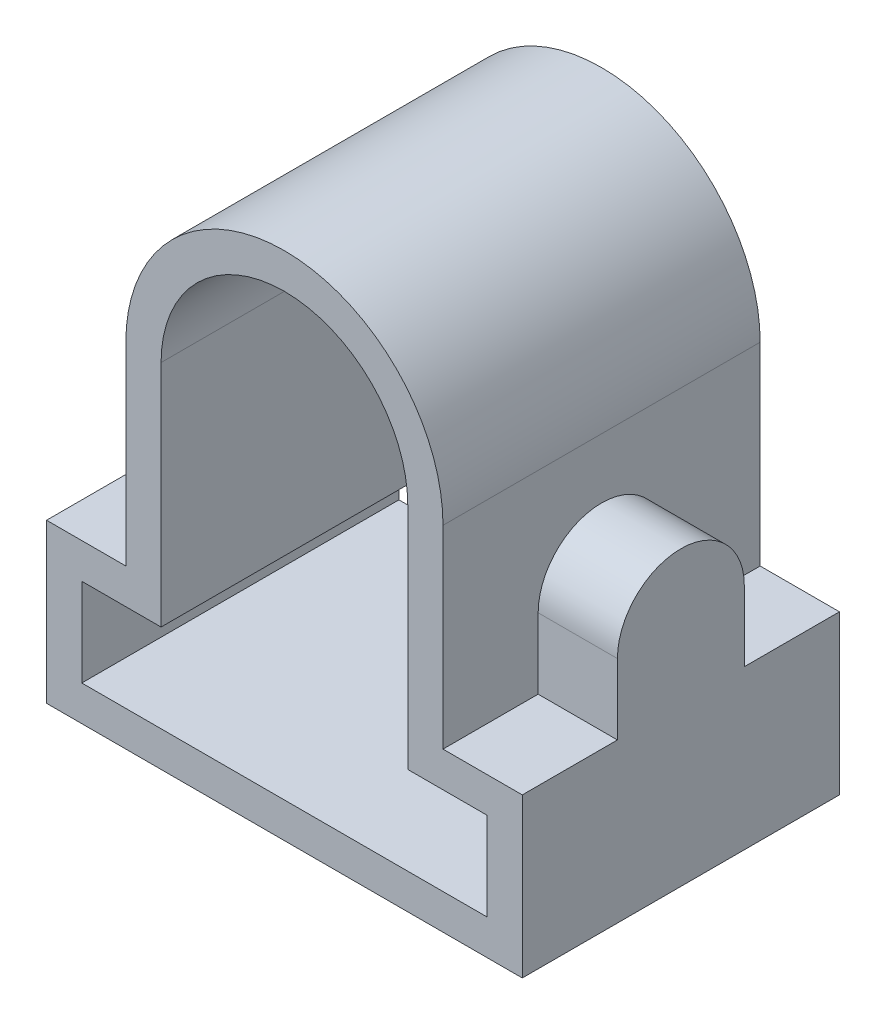
SolidWorks part; units mm, degrees
ref_plane "Płaszczyzna przednia" through (0, 0, 0) normal (0, 0, 1) x (1, 0, 0)
ref_plane "Płaszczyzna górna" through (0, 0, 0) normal (0, 1, 0) x (1, 0, 0)
ref_plane "Płaszczyzna prawa" through (0, 0, 0) normal (1, 0, 0) x (0, 0, -1)
sketch "Szkic1" plane through (0, 0, 0) normal (0, 0, 1) x (1, 0, 0)
  line L0 (0, 0) -> (0, 100) construction
  line L1 (67.5, 0) -> (-67.5, 0)
  line L2 (-67.5, 0) -> (-67.5, 45)
  line L3 (-67.5, 45) -> (-45, 45)
  line L4 (-45, 45) -> (-45, 100)
  line L5 (67.5, 0) -> (67.5, 45)
  line L6 (67.5, 45) -> (45, 45)
  line L7 (45, 45) -> (45, 100)
  line L8 (35, 35) -> (35, 100)
  line L9 (57.5, 35) -> (35, 35)
  line L10 (57.5, 10) -> (57.5, 35)
  line L11 (57.5, 10) -> (-57.5, 10)
  line L12 (-57.5, 10) -> (-57.5, 35)
  line L13 (-57.5, 35) -> (-35, 35)
  line L14 (-35, 35) -> (-35, 100)
  arc A0 (-45, 100) -> (45, 100) centre (0, 100) cw
  arc A1 (-35, 100) -> (35, 100) centre (0, 100) cw
  point P12 (0, 0)
  point P13 (0, 0)
  point P14 (0, 0)
  dimension "D4" = 45
  dimension "D1" = 135
  dimension "D2" = 100
  dimension "D3" = 45
  dimension "D5" = 10
extrude "Dodanie-wyciągnięcie1" add sketch "Szkic1" along normal mid plane 90
sketch "Szkic2" plane through (67.5, 0, 0) normal (1, 0, 0) x (0, 0, -1)
  line L0 (0, 0) -> (0, 65) construction
  line L1 (-45, 0) -> (45, 0) construction
  line L2 (-18, 65) -> (-18, 45)
  line L3 (-45, 45) -> (45, 45) construction
  line L4 (18, 65) -> (18, 45)
  line L5 (18, 45) -> (-18, 45)
  circle A0 centre (0, 65) radius 18
  dimension "D1" = 36
  dimension "D2" = 65
extrude "Dodanie-wyciągnięcie3" add sketch "Szkic2" against normal up to surface (22.5 mm away)
